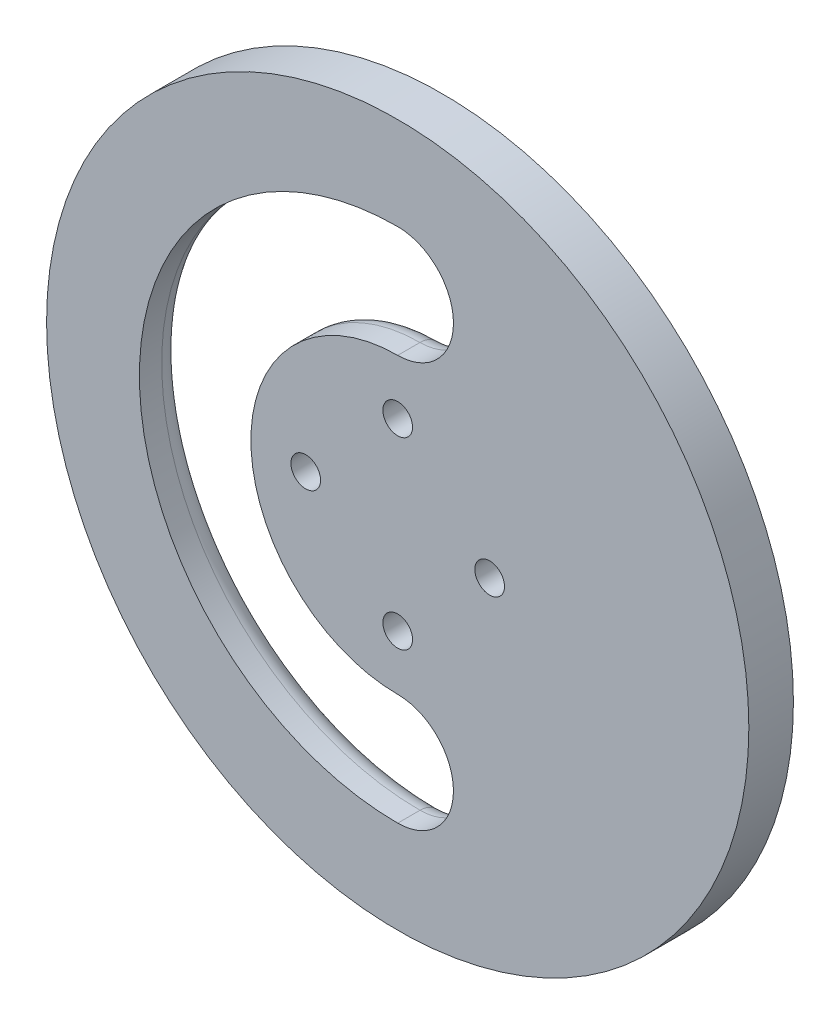
SolidWorks part; units mm, degrees
material "Nylon PA 12"
ref_plane "Front Plane" through (0, 0, 0) normal (0, 0, 1) x (1, 0, 0)
ref_plane "Top Plane" through (0, 0, 0) normal (0, 1, 0) x (1, 0, 0)
ref_plane "Right Plane" through (0, 0, 0) normal (1, 0, 0) x (0, 0, -1)
sketch "Sketch1" plane through (0, 0, 0) normal (0, 0, 1) x (1, 0, 0)
  line L0 (0, 8.25) -> (0, -8.25) construction
  line L1 (-8.25, 0) -> (8.25, 0) construction
  circle A0 centre (0, 8.25) radius 1.33 construction
  circle A1 centre (8.25, 0) radius 1.33 construction
  circle A2 centre (0, -8.25) radius 1.33 construction
  circle A3 centre (-8.25, 0) radius 1.33 construction
  circle A5 centre (0, 0) radius 31.5
  point P5 (0, 0)
  point P6 (0, 0)
  dimension "D1" = 4
extrude "Elbow Plate" add sketch "Sketch1" along normal blind 4
sketch "Sketch2" plane through (0, 0, 0) normal (0, 0, -1) x (-1, 0, 0)
  line L0 (8.25, 0) -> (-8.25, 0) construction
  circle A0 centre (0, 0) radius 8.25 construction
  circle A1 centre (0, 8.25) radius 1.33
  circle A2 centre (8.25, 0) radius 1.33
  circle A3 centre (0, -8.25) radius 1.33
  circle A4 centre (-8.25, 0) radius 1.33
  dimension "D2" = 2.66
  dimension "D3" = 16.5
  dimension "D1" = 4
extrude "Horn Screw Holes" cut sketch "Sketch2" against normal blind 4
sketch "Sketch3" plane through (0, 0, 0) normal (0, 0, -1) x (-1, 0, 0)
  line L0 (8.25, 0) -> (-8.25, 0) construction
  circle A0 centre (0, 0) radius 26.5 construction
  circle A1 centre (0, 0) radius 31.5 construction
  circle A8 centre (22.9497, 13.25) radius 1.33
  circle A9 centre (0, 26.5) radius 1.33
  circle A15 centre (22.9497, -13.25) radius 1.33
  circle A16 centre (0, -26.5) radius 1.33
  circle A17 centre (-22.9497, -13.25) radius 1.33
  circle A18 centre (-22.9497, 13.25) radius 1.33
  dimension "D1" = 5
  dimension "D2" = 6
  dimension "D3" = 53
  dimension "D4" = 2.66
extrude "Screw Holes" cut sketch "Sketch3" against normal blind 3
sketch "Sketch4" plane through (0, 0, 4) normal (0, 0, 1) x (1, 0, 0)
  line L0 (0, 0) -> (15.3714, -15.3714) construction
  line L1 (-8.25, 0) -> (8.25, 0) construction
  line L2 (0, 0) -> (16.7612, 16.7612) construction
  line L3 (0, -8.25) -> (0, -33.1782) construction
  line L4 (0, 8.25) -> (0, 26.5) construction
  arc A1 (0, -23.1723) -> (0, -13.17) centre (0, -18.1712) ccw
  arc A2 (0, 13.17) -> (0, 23.1723) centre (0, 18.1712) ccw
  arc A3 (0, 18.1712) -> (4.9536, -17.4829) centre (0, 0) ccw construction
  arc A4 (0, 13.17) -> (0, -13.17) centre (0, 0) ccw
  arc A5 (0, 23.1723) -> (0, -23.1723) centre (0, 0) ccw
  dimension "D4" = 13.17
  dimension "D5" = 23.1723
  dimension "D1" = 270
  dimension "D2" = 45
extrude "Cable Slot" cut sketch "Sketch4" against normal blind 4
fillet "Fillet1" radius 2 4 edges at (5.0012, 18.1712, 0) (-13.17, 0, 0) (5.0012, -18.1712, 0) (-23.1723, 0, 0)
